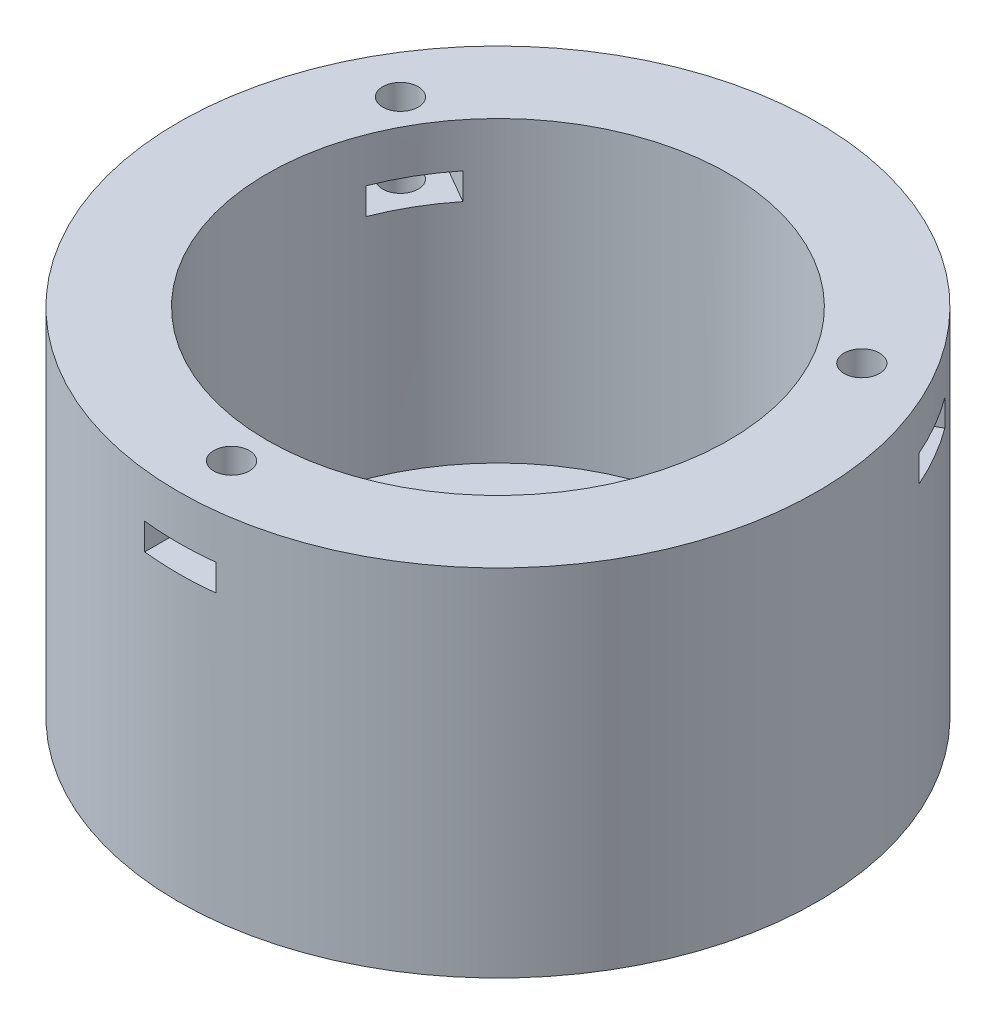
SolidWorks part; units mm, degrees
ref_plane "Front Plane" through (0, 0, 0) normal (0, 0, 1) x (1, 0, 0)
ref_plane "Top Plane" through (0, 0, 0) normal (0, 1, 0) x (1, 0, 0)
ref_plane "Right Plane" through (0, 0, 0) normal (1, 0, 0) x (0, 0, -1)
sketch "Sketch1" plane through (0, 0, 0) normal (0, 1, 0) x (1, 0, 0)
  circle A0 centre (0, 0) radius 57.15
  dimension "D1" = 114.3
extrude "Boss-Extrude1" add sketch "Sketch1" along normal blind 63.5
sketch "Sketch2" plane through (0, 63.5, 0) normal (0, 1, 0) x (1, 0, 0)
  circle A0 centre (0, 0) radius 41.275
  dimension "D1" = 82.55
extrude "Cut-Extrude1" cut sketch "Sketch2" against normal offset from surface (53.34 mm away) 10.16 up to face at (0, 0, 57.15)
sketch "Sketch3" plane through (0, 63.5, 0) normal (0, 1, 0) x (1, 0, 0)
  circle A0 centre (0, 0) radius 47.625 construction
  dimension "D1" = 95.25
hole_wizard "1/4 (0.25) Diameter Hole4" positions "Sketch5" profile "Sketch6" hole size "1/4" standard "ANSI Inch"
sketch "Sketch5" plane through (0, 63.5, 0) normal (0, 1, 0) x (1, 0, 0)
  line L0 (-41.2445, 23.8125) -> (41.2445, 23.8125) construction
  line L1 (41.2445, 23.8125) -> (0, -47.625) construction
  line L2 (0, -47.625) -> (-41.2445, 23.8125) construction
  circle A0 centre (0, 0) radius 47.625 construction
  point P0 (-41.2445, 23.8125)
  point P2 (0, -47.625)
  point P4 (41.2445, 23.8125)
  dimension "D1" = 82.4889
sketch "Sketch6" plane through (-41.2445, 63.5, -23.8125) normal (1, 0, 0) x (0, 0, 1)
  line L0 (0, 0) -> (0, 27.3077)
  line L1 (0, 27.3077) -> (3.175, 25.4)
  line L2 (3.175, 25.4) -> (3.175, 0)
  line L5 (3.175, 0) -> (0, 0)
  line L10 (0, 27.3077) -> (-3.175, 25.4) construction
  line L11 (0, -6.35) -> (0, 107.95) construction
  dimension "Hole Dia." = 6.35
  dimension "Hole Depth" = 25.4
  dimension "Drill Angle" = 118
sketch "Sketch7" plane through (0, 0, 0) normal (0, 0, 1) x (1, 0, 0)
  circle A0 centre (0, 15.24) radius 3.81
  dimension "D1" = 7.62
  dimension "D2" = 15.24
extrude "Cut-Extrude2" cut sketch "Sketch7" against normal through all
hole_wizard "Ø4.0mm Dowel Hole1" positions "3DSketch1" profile "Sketch8" hole size "Ø4.0" standard "ANSI Metric" end condition through all
sketch3d "3DSketch1"
  line L0 (-5, 0, 15.9385) -> (5, 0, -33.5615) construction
  line L2 (5, 0, 15.9385) -> (-5, 0, -33.5615) construction
  circle A0 centre (0, 0, 0) radius 57.15 construction
  point P0 (-5, 0, 15.9385)
  point P2 (5, 0, 15.9385)
  point P4 (5, 0, -33.5615)
  point P6 (-5, 0, -33.5615)
  point P29 (0, 0, -8.8115)
  point P33 (0, 57.15, 0)
  dimension "D1" = 10
  dimension "D2" = 49.5
sketch "Sketch8" plane through (-5, 0, 15.9385) normal (1, 0, 0) x (0, 0, -1)
  line L0 (0, 0) -> (0, 63.5)
  line L1 (0, 63.5) -> (2, 63.5)
  line L2 (2, 63.5) -> (2, 0)
  line L5 (2, 0) -> (0, 0)
  line L11 (0, -6.35) -> (0, 107.95) construction
  dimension "Thru Hole Dia." = 4
  dimension "Thru Hole Depth" = 63.5
sketch "Sketch9" plane through (0, 0, 0) normal (0, -1, 0) x (1, 0, 0)
  line L1 (-1.5, 12.4385) -> (-8.5, 12.4385)
  line L2 (-1.5, 12.4385) -> (-1.5, 19.4385)
  line L3 (-1.5, 19.4385) -> (-8.5, 19.4385)
  line L4 (-8.5, 12.4385) -> (-8.5, 19.4385)
  line L5 (-1.5, 12.4385) -> (-8.5, 19.4385) construction
  line L6 (-1.5, 19.4385) -> (-8.5, 12.4385) construction
  line L11 (8.5, 12.4385) -> (1.5, 12.4385)
  line L12 (8.5, 12.4385) -> (8.5, 19.4385)
  line L13 (8.5, -37.0615) -> (1.5, -37.0615)
  line L14 (8.5, -37.0615) -> (8.5, -30.0615)
  line L15 (8.5, -30.0615) -> (1.5, -30.0615)
  line L16 (1.5, -37.0615) -> (1.5, -30.0615)
  line L17 (8.5, -37.0615) -> (1.5, -30.0615) construction
  line L18 (8.5, -30.0615) -> (1.5, -37.0615) construction
  line L19 (-1.5, -37.0615) -> (-8.5, -37.0615)
  line L20 (-1.5, -37.0615) -> (-1.5, -30.0615)
  line L21 (-1.5, -30.0615) -> (-8.5, -30.0615)
  line L22 (-8.5, -37.0615) -> (-8.5, -30.0615)
  line L23 (-1.5, -37.0615) -> (-8.5, -30.0615) construction
  line L24 (-1.5, -30.0615) -> (-8.5, -37.0615) construction
  line L25 (8.5, 19.4385) -> (1.5, 19.4385)
  line L26 (1.5, 12.4385) -> (1.5, 19.4385)
  line L27 (8.5, 12.4385) -> (1.5, 19.4385) construction
  line L28 (8.5, 19.4385) -> (1.5, 12.4385) construction
  point P0 (-5, 15.9385)
  point P7 (5, 15.9385)
  point P12 (5, -33.5615)
  point P18 (-5, -33.5615)
  dimension "D1" = 7
  dimension "D2" = 7
extrude "Cut-Extrude3" cut sketch "Sketch9" against normal blind 3.5
ref_plane "Plane1" through (0, 50.8, 0) normal (0, 1, 0) x (1, 0, 0)
sketch "Sketch12" plane through (0, 50.8, 0) normal (0, 1, 0) x (1, 0, 0)
  line L1 (-38.4946, 14.8925) -> (-32.1446, 25.8911)
  line L3 (-48.6424, 35.4161) -> (-54.9924, 24.4175)
  line L5 (48.6424, 35.4161) -> (54.9924, 24.4175)
  line L7 (38.4946, 14.8925) -> (32.1446, 25.8911)
  line L8 (-48.6424, 35.4161) -> (-32.1446, 25.8911)
  line L13 (6.35, -59.8336) -> (-6.35, -59.8336)
  line L14 (6.35, -59.8336) -> (6.35, -40.7836)
  line L15 (6.35, -40.7836) -> (-6.35, -40.7836)
  line L16 (-6.35, -59.8336) -> (-6.35, -40.7836)
  line L19 (-54.9924, 24.4175) -> (-38.4946, 14.8925)
  line L20 (48.6424, 35.4161) -> (32.1446, 25.8911)
  line L21 (54.9924, 24.4175) -> (38.4946, 14.8925)
  line L22 (0, 0) -> (51.8174, 29.9168) construction
  line L23 (0, 0) -> (-51.8174, 29.9168)
  circle A1 centre (0, 0) radius 41.275 construction
  circle A2 centre (0, 0) radius 41.275 construction
  point P14 (0, -47.625)
  point P15 (0, -47.625)
  dimension "D1" = 12.7
  dimension "D2" = 19.05
extrude "Cut-Extrude4" cut sketch "Sketch12" along normal blind 4.7625 contours L1 L23 L3 L19 | L23 L1 L8 L3 | L7 L22 L5 L20 | L22 L7 L21 L5 | L16 L13 L14 L15
